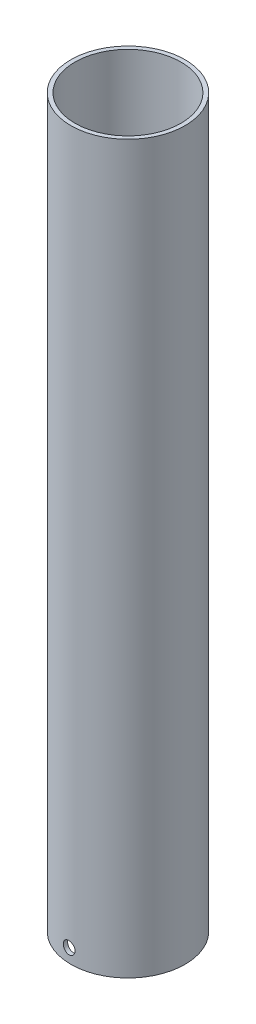
SolidWorks part; units mm, degrees
ref_plane "前视基准面" through (0, 0, 0) normal (0, 0, 1) x (1, 0, 0)
ref_plane "上视基准面" through (0, 0, 0) normal (0, 1, 0) x (1, 0, 0)
ref_plane "右视基准面" through (0, 0, 0) normal (1, 0, 0) x (0, 0, -1)
sketch "草图1" plane through (0, 0, 0) normal (0, 1, 0) x (1, 0, 0)
  circle A0 centre (0, 0) radius 14
  circle A1 centre (0, 0) radius 13
  dimension "D1" = 28
  dimension "D2" = 26
extrude "凸台-拉伸1" add sketch "草图1" along normal blind 178
sketch "草图2" plane through (-0.6113, 0, 17.4893) normal (-0.0349, 0, 0.9994) x (0.9994, 0, 0.0349)
  circle A0 centre (0, 3.3029) radius 1.5 construction
  circle A1 centre (0, 3.3029) radius 1.5
extrude "切除-拉伸1" cut sketch "草图2" against normal through all both and the other way through all
